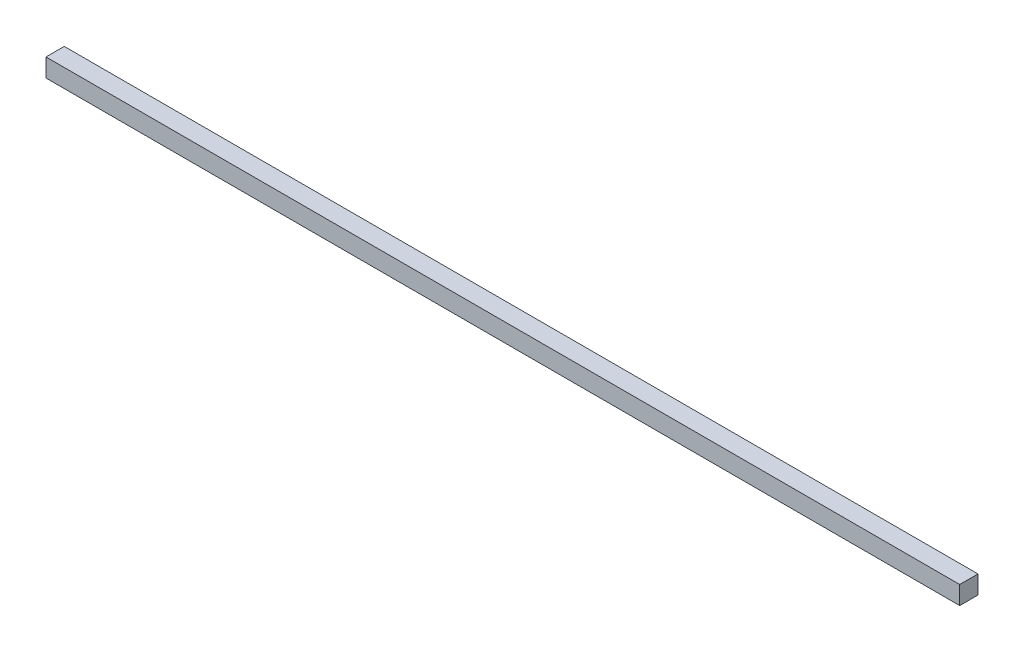
SolidWorks part; units mm, degrees
ref_plane "Front Plane" through (0, 0, 0) normal (0, 0, 1) x (1, 0, 0)
ref_plane "Top Plane" through (0, 0, 0) normal (0, 1, 0) x (1, 0, 0)
ref_plane "Right Plane" through (0, 0, 0) normal (1, 0, 0) x (0, 0, -1)
sketch "Sketch2" plane through (0, 0, 0) normal (0, 1, 0) x (1, 0, 0)
  line L0 (0, 0) -> (1000, 0)
  line L1 (1000, 0) -> (1000, 20)
  line L2 (1000, 20) -> (0, 20)
  line L3 (0, 20) -> (0, 0)
  dimension "D1" = 1000
  dimension "D2" = 20
extrude "Boss-Extrude1" add sketch "Sketch2" along normal blind 20
